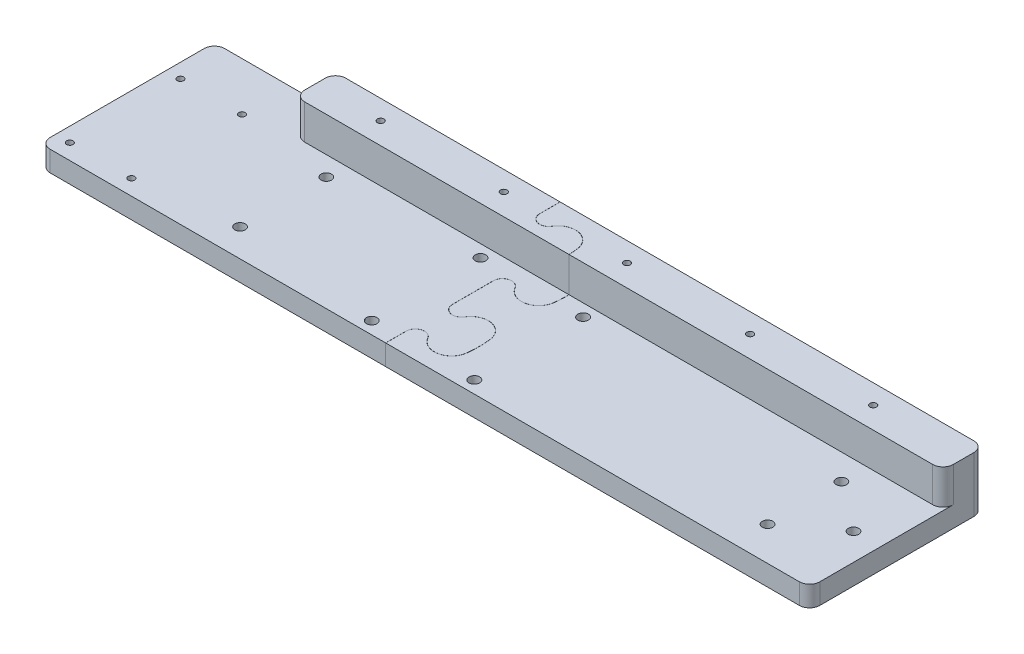
SolidWorks part; units mm, degrees
other "FlangeEnd"
other "MotorEnd"
ref_plane "Front Plane" through (0, 0, 0) normal (0, 0, 1) x (1, 0, 0)
ref_plane "Top Plane" through (0, 0, 0) normal (0, 1, 0) x (1, 0, 0)
ref_plane "Right Plane" through (0, 0, 0) normal (1, 0, 0) x (0, 0, -1)
sketch "Sketch1" plane through (0, 0, 0) normal (0, 1, 0) x (1, 0, 0)
  line L1 (0, 0) -> (375, 0)
  line L2 (0, 0) -> (0, 85)
  line L3 (0, 85) -> (375, 85)
  line L4 (375, 0) -> (375, 85)
  dimension "D1" = 375
  dimension "D2" = 85
extrude "Boss-Extrude1" add sketch "Sketch1" along normal blind 6
sketch "Sketch2" plane through (0, 6, 0) normal (0, 1, 0) x (1, 0, 0)
  line L0 (375, 0) -> (375, 85) construction
  line L1 (59, 85) -> (375, 85)
  line L2 (59, 85) -> (59, 65)
  line L3 (59, 65) -> (375, 65)
  line L4 (375, 85) -> (375, 65)
  dimension "D1" = 316
  dimension "D2" = 20
extrude "Boss-Extrude3" add sketch "Sketch2" along normal blind 17 contours L1 L4 L3 L2
sketch "Sketch3" plane through (0, 6, 0) normal (0, 1, 0) x (1, 0, 0)
  line L0 (59, 85) -> (0, 85) construction
  line L1 (0, 85) -> (0, 0) construction
  line L2 (7, 7.55) -> (37, 7.55) construction
  line L3 (37, 7.55) -> (37, 61.45) construction
  line L4 (37, 61.45) -> (7, 61.45) construction
  line L5 (7, 61.45) -> (7, 7.55) construction
  line L6 (84, 13.5) -> (84, 55.5) construction
  line L7 (338, 52.4871) -> (338, 16.5232) construction
  line L8 (338, 34.5051) -> (361.8969, 34.5051) construction
  line L9 (59, 85) -> (375, 85) construction
  line L10 (90.5, 75.5) -> (150.5, 75.5) construction
  line L11 (150.5, 75.5) -> (210.5, 75.5) construction
  line L12 (210.5, 75.5) -> (270.5, 75.5) construction
  line L13 (270.5, 75.5) -> (330.5, 75.5) construction
  circle A0 centre (7, 61.45) radius 1.575
  circle A1 centre (7, 7.55) radius 1.575
  circle A2 centre (37, 7.55) radius 1.575
  circle A3 centre (37, 61.45) radius 1.575
  circle A4 centre (84, 55.5) radius 2.55
  circle A5 centre (84, 13.5) radius 2.55
  circle A6 centre (338, 52.4871) radius 2.55
  circle A7 centre (361.8969, 34.5051) radius 2.55
  circle A8 centre (338, 16.5232) radius 2.55
  circle A9 centre (90.5, 75.5) radius 1.6
  circle A10 centre (150.5, 75.5) radius 1.6
  circle A11 centre (210.5, 75.5) radius 1.6
  circle A12 centre (270.5, 75.5) radius 1.6
  circle A13 centre (330.5, 75.5) radius 1.6
  dimension "D1" = 3.15
  dimension "D6" = 5.1
  dimension "D8" = 5.1
  dimension "D13" = 3.2
  dimension "D2" = 23.55
  dimension "D3" = 53.9
  dimension "D4" = 30
  dimension "D5" = 7
  dimension "D7" = 42
  dimension "D9" = 84
  dimension "D10" = 338
  dimension "D11" = 35.9639
  dimension "D12" = 23.8969
  dimension "D14" = 60
  dimension "D15" = 60
  dimension "D16" = 60
  dimension "D17" = 60
  dimension "D18" = 9.5
  dimension "D19" = 90.5
  dimension "D20" = 32.5129
  dimension "D21" = 29.5
extrude "Mount Holes" cut sketch "Sketch3" against normal through all both and the other way through all contours A9
sketch "Sketch4" plane through (0, 0, 0) normal (0, -1, 0) x (1, 0, 0)
  line L4 (0, 0) -> (0, -85)
  line L5 (0, -85) -> (375, -85)
  line L6 (375, -85) -> (375, 0)
  line L7 (375, 0) -> (0, 0)
  line L8 (0, 0) -> (0, -85)
  line L9 (0, -85) -> (375, -85)
  line L10 (375, -85) -> (375, 0)
  line L11 (375, 0) -> (0, 0)
  circle A0 centre (7, -7.55) radius 3.575
  circle A1 centre (37, -7.55) radius 3.575
  circle A2 centre (84, -13.5) radius 5.075
  circle A3 centre (84, -55.5) radius 5.075
  circle A4 centre (37, -61.45) radius 3.575
  circle A5 centre (7, -61.45) radius 3.575
  circle A6 centre (90.5, -75.5) radius 3.575
  circle A7 centre (150.5, -75.5) radius 3.575
  circle A8 centre (210.5, -75.5) radius 3.575
  circle A9 centre (270.5, -75.5) radius 3.575
  circle A10 centre (330.5, -75.5) radius 3.575
  circle A11 centre (338, -52.4871) radius 5.075
  circle A12 centre (361.8969, -34.5051) radius 5.075
  circle A13 centre (338, -16.5232) radius 5.075
  dimension "D1" = 7.15
  dimension "D2" = 7.15
  dimension "D3" = 10.15
  dimension "D4" = 0
extrude "Boss-Extrude4" add sketch "Sketch4" along normal blind 4
fillet "Fillet1" radius 5 7 edges at (375, 9.5, -85) (375, 14.5, -65) (375, 1, 0) (59, 14.5, -85) (59, 14.5, -65) (0, 1, 0) (0, 1, -85)
sketch "Sketch7" plane through (0, -4, 0) normal (0, -1, 0) x (1, 0, 0)
  line L0 (192.7645, -21.25) -> (192.7645, -35.1728) construction
  line L1 (370, 0) -> (5, 0) construction
  line L2 (0, -42.5) -> (375, -42.5) construction
  line L3 (0, -5) -> (0, -80) construction
  line L4 (375, -80) -> (375, -5) construction
  line L5 (149.6901, -42.5) -> (149.6901, 0) construction
  line L6 (149.6901, -21.25) -> (215.9921, -21.25) construction
  line L7 (168.4297, -9.9687) -> (168.4297, 0)
  line L8 (168.4297, -32.5313) -> (168.4297, -52.4687)
  line L9 (192.7645, -63.75) -> (192.7645, -49.8272) construction
  line L10 (168.4297, -75.0313) -> (168.4297, -85)
  line L11 (168.4797, -75.0313) -> (168.4797, -85)
  line L12 (168.4797, -32.5313) -> (168.4797, -52.4687)
  line L13 (168.4797, -9.9687) -> (168.4797, 0)
  line L14 (168.4297, -85) -> (168.4797, -85)
  line L15 (168.4297, 0) -> (168.4797, 0)
  arc A0 (192.4091, -26.9917) -> (192.4091, -15.5083) centre (146.212, -21.25) ccw
  arc A1 (192.4091, -15.5083) -> (176.7645, -12.25) centre (184.0306, -16.5496) ccw
  arc A2 (176.7645, -12.25) -> (168.4297, -9.9687) centre (172.9093, -9.9687) cw
  arc A3 (176.7645, -30.25) -> (168.4297, -32.5313) centre (172.9093, -32.5313) ccw
  arc A4 (192.4091, -26.9917) -> (176.7645, -30.25) centre (184.0306, -25.9504) cw
  arc A5 (192.4091, -58.0083) -> (176.7645, -54.75) centre (184.0306, -59.0496) ccw
  arc A6 (176.7645, -54.75) -> (168.4297, -52.4687) centre (172.9093, -52.4687) cw
  arc A7 (176.7645, -72.75) -> (168.4297, -75.0313) centre (172.9093, -75.0313) ccw
  arc A8 (192.4091, -69.4917) -> (176.7645, -72.75) centre (184.0306, -68.4504) cw
  arc A9 (192.4091, -58.0083) -> (192.4091, -69.4917) centre (146.212, -63.75) cw
  arc A10 (176.7215, -72.7755) -> (168.4797, -75.0313) centre (172.9093, -75.0313) ccw
  arc A11 (192.4587, -69.4979) -> (176.7215, -72.7755) centre (184.0306, -68.4504) cw
  arc A12 (192.4587, -58.0021) -> (192.4587, -69.4979) centre (146.212, -63.75) cw
  arc A13 (192.4587, -58.0021) -> (176.7215, -54.7245) centre (184.0306, -59.0496) ccw
  arc A14 (176.7215, -54.7245) -> (168.4797, -52.4687) centre (172.9093, -52.4687) cw
  arc A15 (176.7215, -30.2755) -> (168.4797, -32.5313) centre (172.9093, -32.5313) ccw
  arc A16 (192.4587, -26.9979) -> (176.7215, -30.2755) centre (184.0306, -25.9504) cw
  arc A17 (192.4587, -26.9979) -> (192.4587, -15.5021) centre (146.212, -21.25) ccw
  arc A18 (192.4587, -15.5021) -> (176.7215, -12.2245) centre (184.0306, -16.5496) ccw
  arc A19 (176.7215, -12.2245) -> (168.4797, -9.9687) centre (172.9093, -9.9687) cw
  point P40 (168.4297, -42.5)
  dimension "D1" = 9
  dimension "D2" = 16
  dimension "D3" = 0.05
extrude "Weird Cut" cut sketch "Sketch7" against normal through all both and the other way through all
sketch "Sketch8" plane through (0, 6, 0) normal (0, 1, 0) x (1, 0, 0)
  line L0 (155.6471, 59) -> (205.6471, 59) construction
  line L1 (155.6471, 6) -> (205.6471, 6) construction
  line L2 (155.6471, 59) -> (155.6471, 6) construction
  line L3 (205.6471, 6) -> (205.6471, 59) construction
  line L4 (192.8145, 21.25) -> (168.4797, 21.25) construction
  line L5 (168.4797, 21.25) -> (168.4797, 42.5) construction
  line L6 (168.4797, 52.4687) -> (168.4797, 32.5313) construction
  line L7 (180.6471, 21.25) -> (180.6471, 59) construction
  line L8 (192.7978, 65) -> (370, 65) construction
  line L9 (168.4797, 0) -> (370, 0) construction
  circle A0 centre (205.6471, 59) radius 2.575
  circle A1 centre (155.6471, 59) radius 2.575
  arc A2 (192.4587, 15.5021) -> (192.4587, 26.9979) centre (146.212, 21.25) ccw construction
  circle A3 centre (205.6471, 6) radius 2.575
  circle A4 centre (155.6471, 6) radius 2.575
  point P12 (180.6471, 21.25)
  point P16 (180.6471, 59)
  dimension "D4" = 5.15
  dimension "D1" = 50
  dimension "D2" = 6
  dimension "D3" = 6
extrude "If you no stay i make u stai breh" cut sketch "Sketch8" against normal through all both and the other way through all
sketch "Sketch9" plane through (0, -4, 0) normal (0, -1, 0) x (1, 0, 0)
  circle A0 centre (155.6471, -6) radius 5.075
  circle A1 centre (205.6471, -6) radius 5.075
  circle A2 centre (205.6471, -59) radius 5.075
  circle A3 centre (155.6471, -59) radius 5.075
  dimension "D1" = 10.15
extrude "yuh" cut sketch "Sketch9" against normal blind 4 and the other way through all
other "Save Bodies1"
